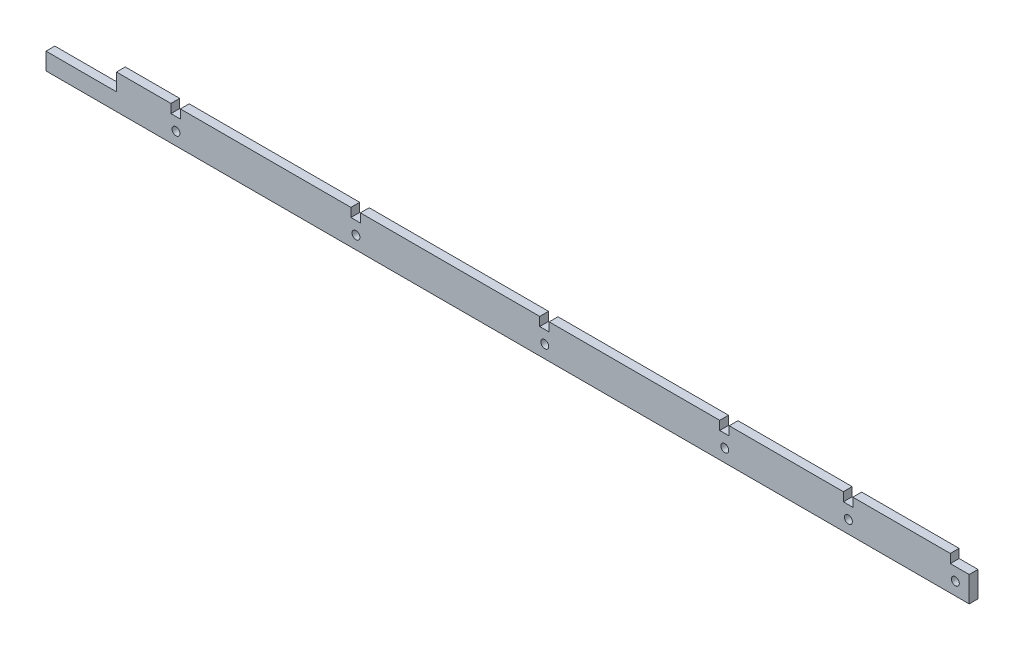
SolidWorks part; units mm, degrees
ref_plane "Front Plane" through (0, 0, 0) normal (0, 0, 1) x (1, 0, 0)
ref_plane "Top Plane" through (0, 0, 0) normal (0, 1, 0) x (1, 0, 0)
ref_plane "Right Plane" through (0, 0, 0) normal (1, 0, 0) x (0, 0, -1)
sketch "Sketch1" plane through (0, 0, 0) normal (0, 0, 1) x (1, 0, 0)
  line L0 (6235.6048, 2712.3838) -> (6235.6048, 2715.5588)
  line L1 (5954.6618, 2715.5588) -> (5954.6618, 2712.3838)
  line L2 (5958.0654, 2715.5588) -> (5958.0654, 2712.3838)
  line L3 (6019.5461, 2715.5588) -> (6019.5461, 2712.3838)
  line L4 (6022.9497, 2715.5588) -> (6022.9497, 2712.3838)
  line L5 (6087.6054, 2715.5588) -> (6087.6054, 2712.3838)
  line L6 (6091.009, 2715.5588) -> (6091.009, 2712.3838)
  line L7 (6152.4897, 2715.5588) -> (6152.4897, 2712.3838)
  line L8 (6155.8933, 2715.5588) -> (6155.8933, 2712.3838)
  line L9 (6197.056, 2715.5588) -> (6197.056, 2712.3838)
  line L10 (6200.4596, 2715.5588) -> (6200.4596, 2712.3838)
  line L11 (6242.412, 2712.3838) -> (6235.6048, 2712.3838)
  line L12 (6200.4596, 2712.3838) -> (6197.056, 2712.3838)
  line L13 (6155.8933, 2712.3838) -> (6152.4897, 2712.3838)
  line L14 (6091.009, 2712.3838) -> (6087.6054, 2712.3838)
  line L15 (6022.9497, 2712.3838) -> (6019.5461, 2712.3838)
  line L16 (5958.0654, 2712.3838) -> (5954.6618, 2712.3838)
  line L17 (6235.6048, 2715.5588) -> (6200.4596, 2715.5588)
  line L18 (6197.056, 2715.5588) -> (6155.8933, 2715.5588)
  line L19 (6152.4897, 2715.5588) -> (6091.009, 2715.5588)
  line L20 (6087.6054, 2715.5588) -> (6022.9497, 2715.5588)
  line L21 (6019.5461, 2715.5588) -> (5958.0654, 2715.5588)
  line L22 (5954.6618, 2715.5588) -> (5935.0339, 2715.5588)
  line L23 (6242.412, 2703.189) -> (5909.6339, 2703.189)
  line L24 (6242.412, 2703.189) -> (6242.412, 2712.3838)
  line L25 (5909.6339, 2709.3739) -> (5909.6339, 2703.189)
  line L26 (5935.0339, 2715.5588) -> (5935.0339, 2709.3739)
  line L27 (5909.6339, 2709.3739) -> (5935.0339, 2709.3739)
  circle A0 centre (5956.4779, 2707.7864) radius 1.4224
  circle A1 centre (6021.3622, 2707.7864) radius 1.4224
  circle A2 centre (6089.4215, 2707.7864) radius 1.4224
  circle A3 centre (6154.3058, 2707.7864) radius 1.4224
  circle A4 centre (6198.8721, 2707.7864) radius 1.4224
  circle A5 centre (6237.4209, 2707.7864) radius 1.4224
extrude "Boss-Extrude1" add sketch "Sketch1" along normal blind 3.175
